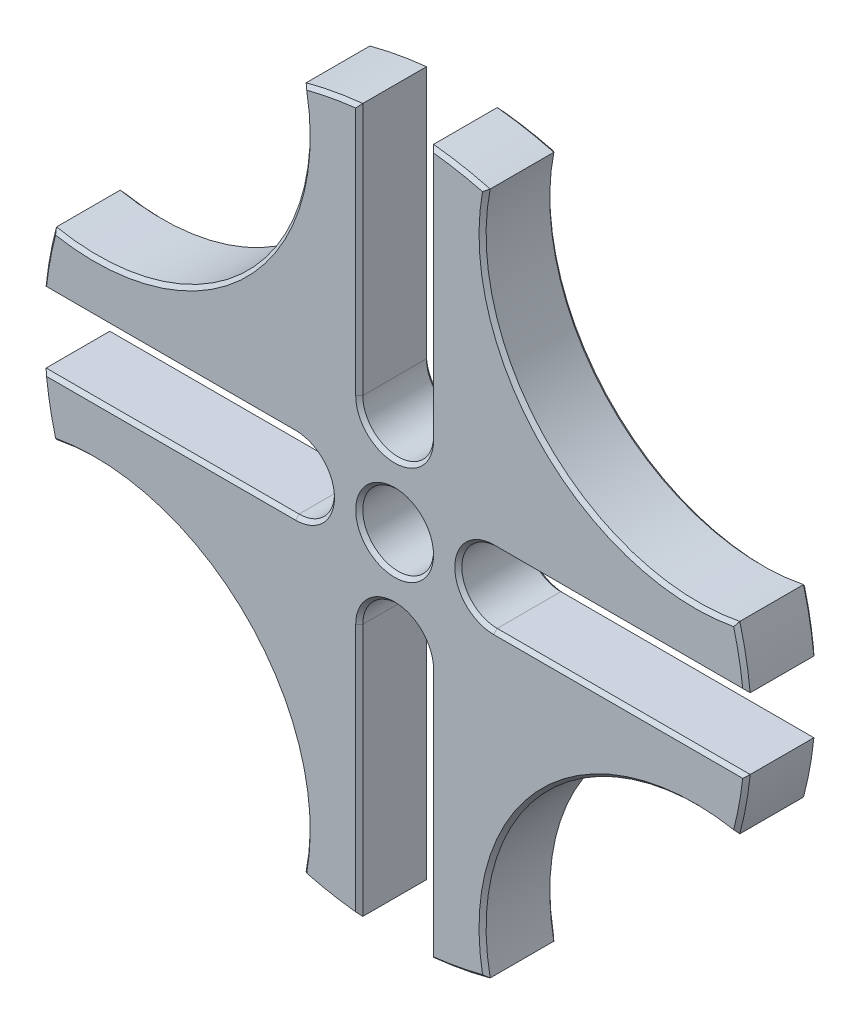
SolidWorks part; units mm, degrees
ref_plane "Ön Düzlem" through (0, 0, 0) normal (0, 0, 1) x (1, 0, 0)
ref_plane "Üst Düzlem" through (0, 0, 0) normal (0, 1, 0) x (1, 0, 0)
ref_plane "Sağ Düzlem" through (0, 0, 0) normal (1, 0, 0) x (0, 0, -1)
sketch "Sketch1" plane through (0, 0, 0) normal (0, 0, 1) x (1, 0, 0)
  circle A0 centre (0, 0) radius 50
  circle A1 centre (0, 0) radius 5
  dimension "D1" = 100
  dimension "D2" = 10
extrude "Boss-Extrude1" add sketch "Sketch1" along normal blind 10
sketch "Sketch2" plane through (0, 0, 10) normal (0, 0, 1) x (1, 0, 0)
  line L0 (0, 79.311) -> (0, -63.2271) construction
  line L1 (-72.315, 0) -> (65.8808, 0) construction
  line L2 (0, 14) -> (0, 86) construction
  line L3 (-5, 14) -> (-5, 86)
  line L4 (5, 14) -> (5, 86)
  line L5 (14, 0) -> (86, 0) construction
  line L6 (14, 5) -> (86, 5)
  line L7 (14, -5) -> (86, -5)
  line L8 (0, -14) -> (0, -86) construction
  line L9 (5, -14) -> (5, -86)
  line L10 (-5, -14) -> (-5, -86)
  line L11 (-14, 0) -> (-86, 0) construction
  line L12 (-14, -5) -> (-86, -5)
  line L13 (-14, 5) -> (-86, 5)
  line L14 (0, 0) -> (42.4264, 42.4264) construction
  arc A0 (-5, 14) -> (5, 14) centre (0, 14) ccw
  arc A1 (5, 86) -> (-5, 86) centre (0, 86) ccw
  circle A2 centre (0, 0) radius 50 construction
  arc A3 (14, 5) -> (14, -5) centre (14, 0) ccw
  arc A4 (86, -5) -> (86, 5) centre (86, 0) ccw
  arc A5 (5, -14) -> (-5, -14) centre (0, -14) ccw
  arc A6 (-5, -86) -> (5, -86) centre (0, -86) ccw
  arc A7 (-14, -5) -> (-14, 5) centre (-14, 0) ccw
  arc A8 (-86, 5) -> (-86, -5) centre (-86, 0) ccw
  circle A9 centre (42.4264, 42.4264) radius 30
  circle A10 centre (42.4264, -42.4264) radius 30
  circle A11 centre (-42.4264, -42.4264) radius 30
  circle A12 centre (-42.4264, 42.4264) radius 30
  point P7 (0, 50)
  point P19 (50, 0)
  point P26 (0, -50)
  point P33 (-50, 0)
  point P38 (0, 0)
  point P48 (0, 0)
  dimension "D1" = 5
  dimension "D6" = 60
  dimension "D2" = 72
  dimension "D4" = 45
  dimension "D5" = 60
  dimension "D3" = 4
  dimension "D7" = 4
extrude "Cut-Extrude1" cut sketch "Sketch2" against normal through all
chamfer "Chamfer1" distance 0.5 angle 45 50 edges at (5, 0, 0) (-21.2132, -21.2132, 0) (-9.0314, -49.1776, 0) (-5, -31.8747, 0) (0, -9, 0) (5, -31.8747, 0) (9.0314, -49.1776, 0) (21.2132, -21.2132, 0) (49.1776, -9.0314, 0) (31.8747, -5, 0) (9, 0, 0) (31.8747, 5, 0) (49.1776, 9.0314, 0) (21.2132, 21.2132, 0) (9.0314, 49.1776, 0) (5, 31.8747, 0) (0, 9, 0) (-5, 31.8747, 0) (-9.0314, 49.1776, 0) (-21.2132, 21.2132, 0) (-49.1776, 9.0314, 0) (-31.8747, 5, 0) (-9, 0, 0) (-31.8747, -5, 0) (-49.1776, -9.0314, 0) (5, 0, 10) (-9, 0, 10) (-31.8747, 5, 10) (-49.1776, 9.0314, 10) (-21.2132, 21.2132, 10) (-9.0314, 49.1776, 10) (-5, 31.8747, 10) (0, 9, 10) (5, 31.8747, 10) (9.0314, 49.1776, 10) (21.2132, 21.2132, 10) (49.1776, 9.0314, 10) (31.8747, 5, 10) (9, 0, 10) (31.8747, -5, 10) (49.1776, -9.0314, 10) (21.2132, -21.2132, 10) (9.0314, -49.1776, 10) (5, -31.8747, 10) (0, -9, 10) (-5, -31.8747, 10) (-9.0314, -49.1776, 10) (-21.2132, -21.2132, 10) (-49.1776, -9.0314, 10) (-31.8747, -5, 10)
sketch "Sketch4" plane through (0, 0, 0) normal (0, 0, -1) x (-1, 0, 0)
  circle A0 centre (0, 0) radius 5
  circle A1 centre (0, 0) radius 8.5
  arc A2 (5.5, -14) -> (-5.5, -14) centre (0, -14) ccw construction
  point P6 (0, -8.5)
  point P9 (0, -8.5)
  dimension "D1" = 10
extrude "Boss-Extrude3" add sketch "Sketch4" along normal blind 10 and the other way blind 5
chamfer "Chamfer2" distance 0.5 angle 45 2 edges at (-8.5, 0, -10) (-5, 0, -10)
